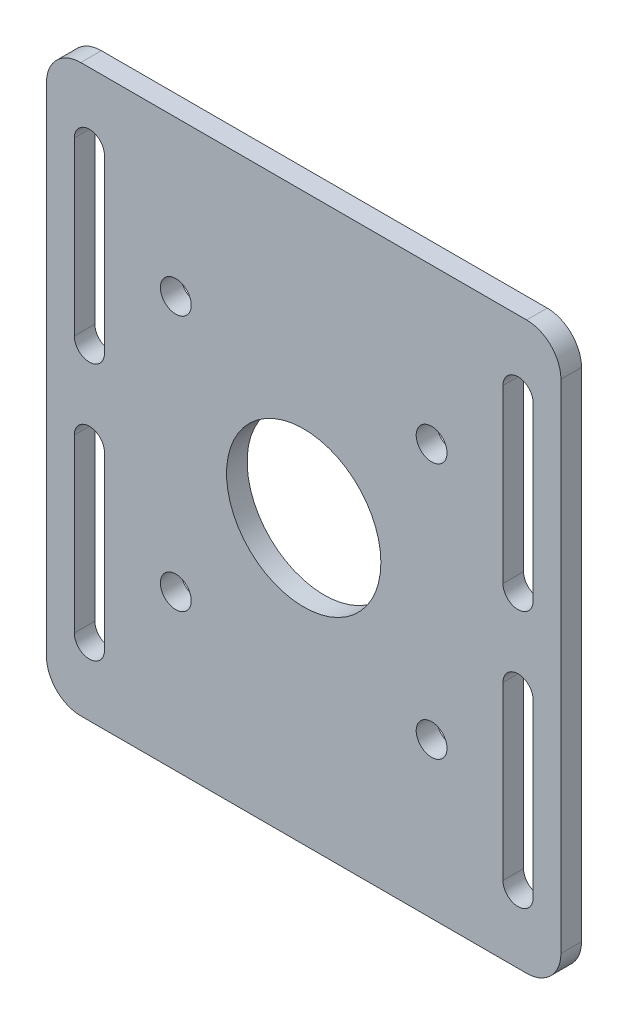
SolidWorks part; units mm, degrees
material "AISI 304"
ref_plane "Спереди" through (0, 0, 0) normal (0, 0, 1) x (1, 0, 0)
ref_plane "Сверху" through (0, 0, 0) normal (0, 1, 0) x (1, 0, 0)
ref_plane "Справа" through (0, 0, 0) normal (1, 0, 0) x (0, 0, -1)
sketch "Эскиз1" plane through (0, 0, 0) normal (0, 0, 1) x (1, 0, 0)
  line L1 (-150, -165) -> (150, -165)
  line L2 (-150, -165) -> (-150, 165)
  line L3 (-150, 165) -> (150, 165)
  line L4 (150, -165) -> (150, 165)
  line L5 (-150, -165) -> (150, 165) construction
  line L6 (-150, 165) -> (150, -165) construction
  circle A0 centre (0, 0) radius 45
  point P0 (0, 0)
  dimension "D3" = 90
  dimension "D1" = 300
  dimension "D2" = 330
extrude "Бобышка-Вытянуть1" add sketch "Эскиз1" along normal mid plane 12
sketch "Эскиз2" plane through (0, 0, 6) normal (0, 0, 1) x (1, 0, 0)
  line L0 (-125, 125) -> (-125, 25) construction
  line L1 (-116.2, 125) -> (-116.2, 25)
  line L2 (-133.8, 125) -> (-133.8, 25)
  line L6 (6.6, 0) -> (-6.6, 0) construction
  line L7 (-125, -125) -> (-125, -25) construction
  line L11 (-116.2, -125) -> (-116.2, -25)
  line L12 (-133.8, -125) -> (-133.8, -25)
  line L13 (0, -6.6) -> (0, 6.6) construction
  line L14 (125, -125) -> (125, -25) construction
  line L15 (116.2, -125) -> (116.2, -25)
  line L16 (133.8, -125) -> (133.8, -25)
  line L17 (125, 125) -> (125, 25) construction
  line L18 (116.2, 125) -> (116.2, 25)
  line L19 (133.8, 125) -> (133.8, 25)
  arc A14 (-116.2, 125) -> (-133.8, 125) centre (-125, 125) ccw
  arc A15 (-133.8, 25) -> (-116.2, 25) centre (-125, 25) ccw
  arc A17 (-116.2, -125) -> (-133.8, -125) centre (-125, -125) cw
  arc A18 (-133.8, -25) -> (-116.2, -25) centre (-125, -25) cw
  arc A19 (116.2, -125) -> (133.8, -125) centre (125, -125) ccw
  arc A20 (133.8, -25) -> (116.2, -25) centre (125, -25) ccw
  arc A21 (116.2, 125) -> (133.8, 125) centre (125, 125) cw
  arc A22 (133.8, 25) -> (116.2, 25) centre (125, 25) cw
  circle A23 centre (0, 0) radius 100 construction
  point P2 (-125, 75)
  point P12 (-125, -75)
  point P21 (125, -75)
  point P28 (125, 75)
  dimension "D2" = 75
  dimension "D3" = 100
  dimension "D1" = 125
  dimension "D5" = 200
  dimension "D4" = 17.6
extrude "Вырез-Вытянуть1" cut sketch "Эскиз2" against normal through all
fillet "Скругление1" radius 20 4 edges at (150, -165, 0) (-150, -165, 0) (150, 165, 0) (-150, 165, 0)
sketch "Эскиз3" plane through (0, 0, 6) normal (0, 0, 1) x (1, 0, 0)
  line L0 (-74.5998, 74.5998) -> (0, 0) construction
  line L1 (0, 0) -> (0, 105.5) construction
  circle A0 centre (0, 0) radius 105.5 construction
  circle A1 centre (-74.5998, 74.5998) radius 9
  circle A2 centre (74.5998, 74.5998) radius 9
  circle A3 centre (74.5998, -74.5998) radius 9
  circle A4 centre (-74.5998, -74.5998) radius 9
  point P15 (0, 0)
  dimension "D1" = 211
  dimension "D3" = 18
  dimension "D2" = 45
  dimension "D4" = 4
extrude "Вырез-Вытянуть2" cut sketch "Эскиз3" against normal up to surface (12 mm away) up to face at (125, 75, -6)
sketch "Эскиз4" plane through (0, 0, 6) normal (0, 0, 1) x (1, 0, 0)
  line L0 (-116.2, 75) -> (116.2, 75) construction
  line L1 (-116.2, 25) -> (-116.2, 125) construction
  line L2 (116.2, 125) -> (116.2, 25) construction
  line L3 (-125, 133.8) -> (-125, 75) construction
  line L4 (-125, 75) -> (-116.2, 75) construction
  line L5 (-116.2, -75) -> (116.2, -75) construction
  line L6 (-116.2, -125) -> (-116.2, -25) construction
  line L7 (116.2, -25) -> (116.2, -125) construction
  line L8 (-125, 75) -> (-125, -75) construction
  line L9 (-125, -75) -> (-116.2, -75) construction
  line L10 (125, 133.8) -> (125, -75) construction
  line L11 (125, -75) -> (116.2, -75) construction
  line L12 (116.2, 75) -> (125, 75) construction
  circle A0 centre (-125, 75) radius 17.25
  arc A1 (-116.2, 125) -> (-133.8, 125) centre (-125, 125) ccw construction
  arc A2 (133.8, 125) -> (116.2, 125) centre (125, 125) ccw construction
  circle A3 centre (125, 75) radius 17.25
  circle A4 centre (125, -75) radius 17.25
  circle A5 centre (-125, -75) radius 17.25
  dimension "D1" = 34.5
split line "Разделяющая линия1" [suppressed]
